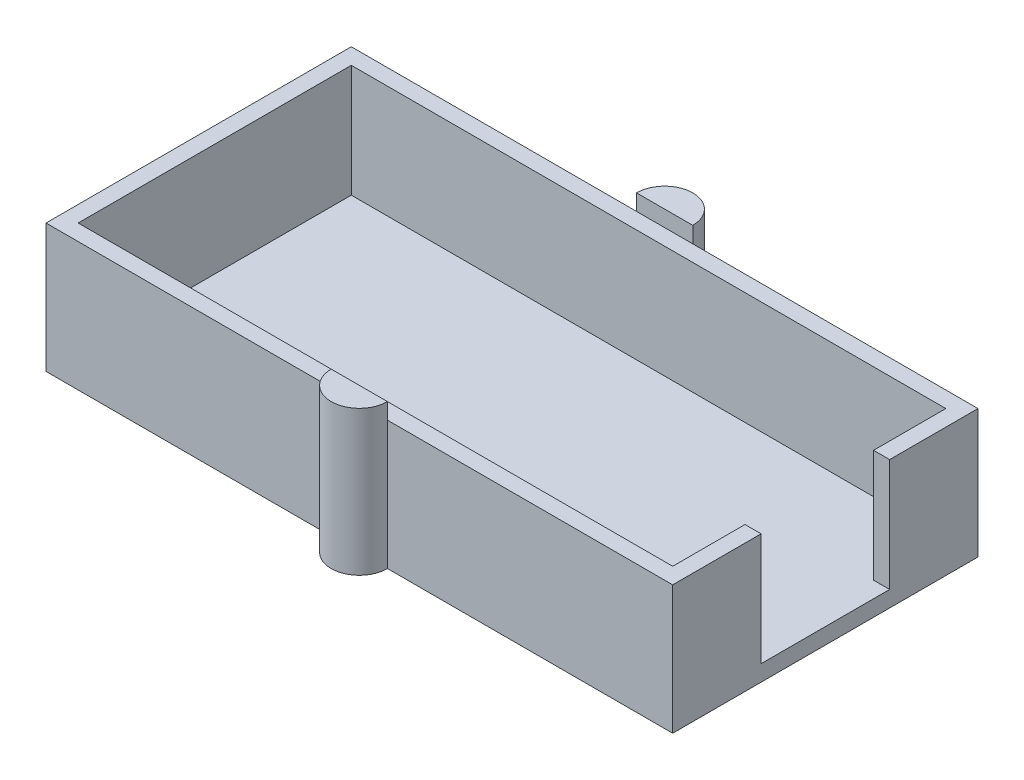
SolidWorks part; units mm, degrees
ref_plane "Front Plane" through (0, 0, 0) normal (0, 0, 1) x (1, 0, 0)
ref_plane "Top Plane" through (0, 0, 0) normal (0, 1, 0) x (1, 0, 0)
ref_plane "Right Plane" through (0, 0, 0) normal (1, 0, 0) x (0, 0, -1)
sketch "Sketch1" plane through (0, 0, 0) normal (0, 1, 0) x (1, 0, 0)
  line L0 (13.1184, 22.1567) -> (52.1184, 22.1567)
  line L1 (14.1184, 21.1567) -> (51.1184, 21.1567)
  line L2 (14.1184, 21.1567) -> (14.1184, 4.1567)
  line L3 (14.1184, 4.1567) -> (51.1184, 4.1567)
  line L4 (51.1184, 21.1567) -> (51.1184, 4.1567)
  line L5 (52.1184, 22.1567) -> (52.1184, 3.1567)
  line L6 (13.1184, 3.1567) -> (52.1184, 3.1567)
  line L7 (13.1184, 22.1567) -> (13.1184, 3.1567)
  dimension "D1" = 37
  dimension "D2" = 17
  dimension "D3" = 1
extrude "Boss-Extrude1" add sketch "Sketch1" along normal blind 7
sketch "Sketch2" plane through (0, 0, 0) normal (0, -1, 0) x (1, 0, 0)
  line L0 (32.6184, -3.1567) -> (32.6184, -22.1567) construction
  line L1 (13.1184, -3.1567) -> (30.8684, -3.1567)
  line L2 (13.1184, -3.1567) -> (13.1184, -22.1567)
  line L3 (13.1184, -22.1567) -> (30.8684, -22.1567)
  line L4 (52.1184, -3.1567) -> (52.1184, -22.1567)
  line L5 (34.3684, -3.1567) -> (52.1184, -3.1567)
  line L6 (34.3684, -22.1567) -> (52.1184, -22.1567)
  arc A0 (34.3684, -3.1567) -> (30.8684, -3.1567) centre (32.6184, -3.1567) ccw
  arc A1 (30.8684, -22.1567) -> (34.3684, -22.1567) centre (32.6184, -22.1567) ccw
  dimension "D1" = 3.5
  dimension "D2" = 3.5
extrude "Boss-Extrude2" add sketch "Sketch2" along normal blind 1
sketch "Sketch3" plane through (0, 0, 0) normal (0, 1, 0) x (1, 0, 0)
  line L0 (30.8684, 22.1567) -> (34.3684, 22.1567)
  line L1 (30.8684, 3.1567) -> (34.3684, 3.1567)
  arc A0 (34.3684, 22.1567) -> (30.8684, 22.1567) centre (32.6184, 22.1567) ccw
  arc A2 (30.8684, 3.1567) -> (34.3684, 3.1567) centre (32.6184, 3.1567) ccw
extrude "Boss-Extrude3" add sketch "Sketch3" along normal blind 8
sketch "Sketch4" plane through (52.1184, 0, 0) normal (1, 0, 0) x (0, 0, -1)
  line L0 (12.6567, 7) -> (12.6567, -1) construction
  line L1 (3.1567, 7) -> (22.1567, 7) construction
  line L2 (22.1567, -1) -> (3.1567, -1) construction
  line L3 (4.1567, 0) -> (21.1567, 0) construction
  line L4 (8.6567, 7) -> (16.6567, 7)
  line L5 (8.6567, 7) -> (8.6567, 0)
  line L6 (8.6567, 0) -> (16.6567, 0)
  line L7 (16.6567, 7) -> (16.6567, 0)
  dimension "D1" = 8
  dimension "D2" = 4
extrude "Cut-Extrude1" cut sketch "Sketch4" against normal blind 8
